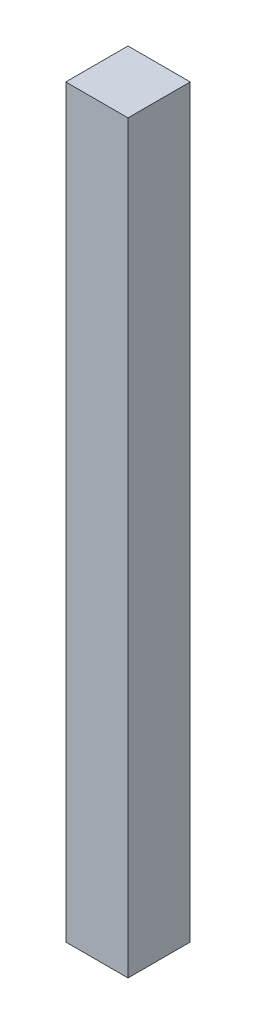
SolidWorks part; units mm, degrees
ref_plane "Front Plane" through (0, 0, 0) normal (0, 0, 1) x (1, 0, 0)
ref_plane "Top Plane" through (0, 0, 0) normal (0, 1, 0) x (1, 0, 0)
ref_plane "Right Plane" through (0, 0, 0) normal (1, 0, 0) x (0, 0, -1)
sketch "Sketch1" plane through (0, 0, 0) normal (0, 1, 0) x (1, 0, 0)
  line L1 (-25.4, -25.4) -> (25.4, -25.4)
  line L2 (-25.4, -25.4) -> (-25.4, 25.4)
  line L3 (-25.4, 25.4) -> (25.4, 25.4)
  line L4 (25.4, -25.4) -> (25.4, 25.4)
  line L5 (-25.4, -25.4) -> (25.4, 25.4) construction
  line L6 (-25.4, 25.4) -> (25.4, -25.4) construction
  point P0 (0, 0)
  dimension "D1" = 50.8
extrude "Boss-Extrude1" add sketch "Sketch1" along normal blind 608.0125
